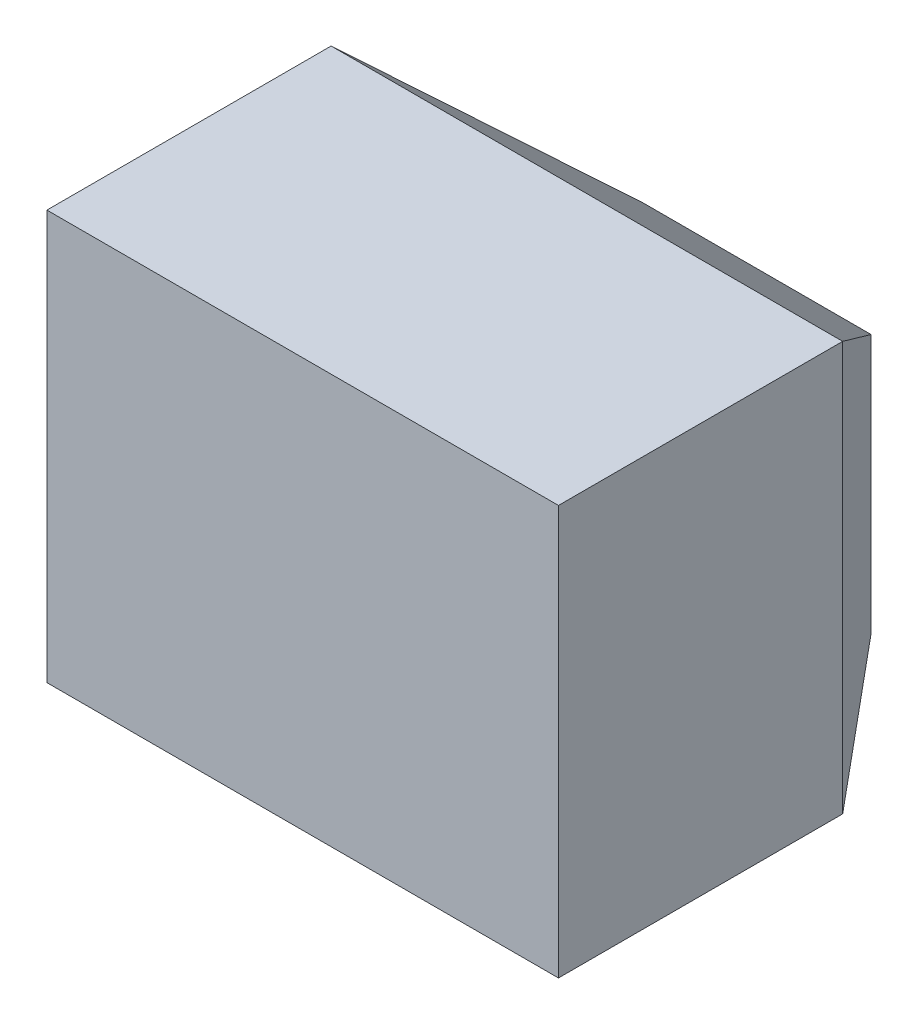
SolidWorks part; units mm, degrees
ref_plane "前视基准面" through (0, 0, 0) normal (0, 0, 1) x (1, 0, 0)
ref_plane "上视基准面" through (0, 0, 0) normal (0, 1, 0) x (1, 0, 0)
ref_plane "右视基准面" through (0, 0, 0) normal (1, 0, 0) x (0, 0, -1)
sketch "草图1" plane through (0, 0, 0) normal (0, 1, 0) x (1, 0, 0)
  line L0 (0, 0) -> (0, 400) construction
  line L1 (-225, 0) -> (225, 0)
  line L2 (225, 0) -> (225, 250)
  line L3 (225, 250) -> (100, 400)
  line L4 (100, 400) -> (-100, 400)
  line L5 (-225, 0) -> (-225, 250)
  line L6 (-225, 250) -> (-100, 400)
  point P7 (0, 400)
  point P10 (0, 400)
  dimension "D1" = 450
  dimension "D2" = 400
  dimension "D3" = 250
  dimension "D4" = 100
extrude "凸台-拉伸1" add sketch "草图1" along normal blind 360
sketch "草图2" plane through (225, 0, 0) normal (1, 0, 0) x (0, 0, -1)
  line L0 (250, 360) -> (400, 227.7124)
  line L1 (400, 360) -> (400, 0) construction
  line L2 (400, 227.7124) -> (400, 360)
  line L3 (400, 360) -> (250, 360)
  dimension "D1" = 200
extrude "切除-拉伸1" cut sketch "草图2" against normal through all
